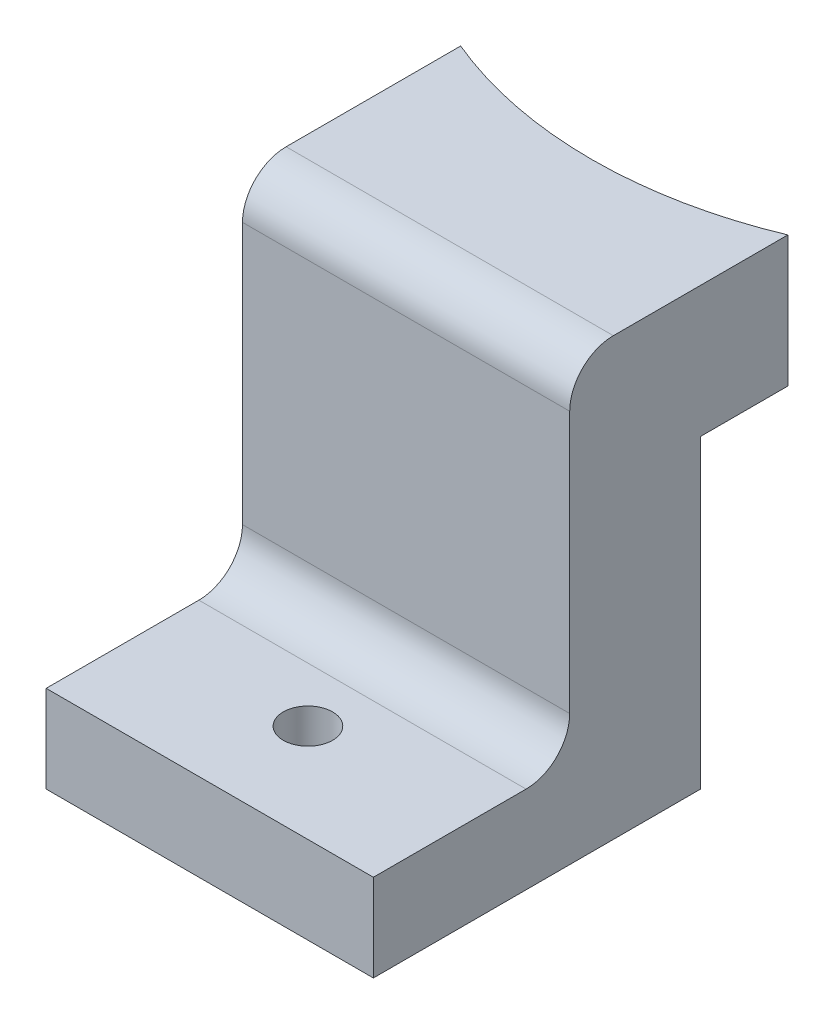
SolidWorks part; units mm, degrees
material "6061 Alloy"
ref_plane "Front Plane" through (0, 0, 0) normal (0, 0, 1) x (1, 0, 0)
ref_plane "Top Plane" through (0, 0, 0) normal (0, 1, 0) x (1, 0, 0)
ref_plane "Right Plane" through (0, 0, 0) normal (1, 0, 0) x (0, 0, -1)
sketch "Sketch1" plane through (0, 0, 0) normal (0, 1, 0) x (1, 0, 0)
  line L0 (7.5, 5) -> (-7.5, -5) construction
  line L1 (-7.5, 5) -> (7.5, 5)
  line L2 (-7.5, 5) -> (-7.5, -5)
  line L3 (-7.5, -5) -> (7.5, -5)
  line L4 (7.5, 5) -> (7.5, -5)
  line L5 (-7.5, 5) -> (7.5, -5) construction
  point P2 (0, 0)
  dimension "D1" = 15
  dimension "D2" = 10
extrude "Boss-Extrude1" add sketch "Sketch1" along normal blind 6
sketch "Sketch2" plane through (0, 6, 0) normal (0, 1, 0) x (1, 0, 0)
  circle A0 centre (0, 23) radius 19.5
  dimension "D1" = 39
extrude "Cut-Extrude1" cut sketch "Sketch2" against normal blind 9
sketch "Sketch12" [suppressed] plane through (0, 6, 0) normal (0, 1, 0) x (1, 0, 0)
  line L2 (-7.5, 5) -> (7.5, 5)
  line L3 (7.5, 5) -> (-7.5, 5) construction
  arc A0 (-7.5, 5) -> (7.5, 5) centre (0, 25.6821) ccw
  dimension "D1" = 44
extrude "Cut-Extrude2" [suppressed] cut sketch "Sketch12" against normal through all
sketch "Sketch3" plane through (0, 6, 0) normal (0, 1, 0) x (1, 0, 0)
  line L0 (-7.5, 5) -> (-7.5, -5) construction
  line L1 (-7.5, 1) -> (7.5, 1)
  line L2 (-7.5, 1) -> (-7.5, -5)
  line L3 (-7.5, -5) -> (7.5, -5)
  line L4 (7.5, 1) -> (7.5, -5)
  line L5 (-7.5, -5) -> (7.5, -5) construction
  line L6 (7.5, -5) -> (7.5, 5) construction
  dimension "D1" = 6
  dimension "D2" = 0
  dimension "D3" = 15
  dimension "D4" = 6
extrude "Boss-Extrude2" add sketch "Sketch3" against normal blind 20
sketch "Sketch4" plane through (0, 0, 5) normal (0, 0, 1) x (1, 0, 0)
  line L0 (-7.5, -14) -> (7.5, -14) construction
  line L1 (-7.5, -10) -> (7.5, -10)
  line L2 (-7.5, -10) -> (-7.5, -14)
  line L3 (-7.5, -14) -> (7.5, -14)
  line L4 (7.5, -10) -> (7.5, -14)
  line L5 (7.5, -14) -> (7.5, 6) construction
  line L6 (-7.5, -14) -> (-7.5, 6) construction
  dimension "D1" = 4
  dimension "D3" = 0
extrude "Boss-Extrude3" add sketch "Sketch4" along normal blind 9
sketch "Sketch9" plane through (0, -14, 0) normal (0, -1, 0) x (1, 0, 0)
  line L0 (0, 14) -> (0, -1) construction
  line L1 (-7.5, 14) -> (7.5, 14) construction
  line L2 (7.5, -1) -> (-7.5, -1) construction
  line L3 (-7.5, 9.5) -> (7.5, 9.5) construction
  line L4 (-7.5, -1) -> (-7.5, 14) construction
  line L5 (7.5, 14) -> (7.5, -1) construction
  point P12 (0, 9.5)
  dimension "D1" = 4.5
hole_wizard "#4-40 Tapped Hole2" positions "Sketch10" profile "Sketch11" tap size "#4-40" standard "ANSI Inch"
sketch "Sketch10" plane through (0, -14, 0) normal (0, -1, 0) x (-1, 0, 0)
  point P0 (0, -9.5)
sketch "Sketch11" plane through (0, -14, 9.5) normal (1, 0, 0) x (0, 0, -1)
  line L0 (0, 0) -> (0, 8.2792)
  line L1 (0, 8.2792) -> (1.1303, 7.6)
  line L2 (1.1303, 7.6) -> (1.1303, 0)
  line L5 (1.1303, 0) -> (0, 0)
  line L10 (0, 8.2792) -> (-1.1303, 7.6) construction
  line L11 (0, -6.35) -> (0, 107.95) construction
  dimension "Tap Drill Dia." = 2.2606
  dimension "Tap Drill Depth" = 7.6
  dimension "Drill Angle" = 118
cosmetic thread "Hole Thread2" parameters "D1"=5.69, "D2"=2.8448
fillet "Fillet2" radius 2 2 edges at (0, -10, 5) (0, 6, 5)
